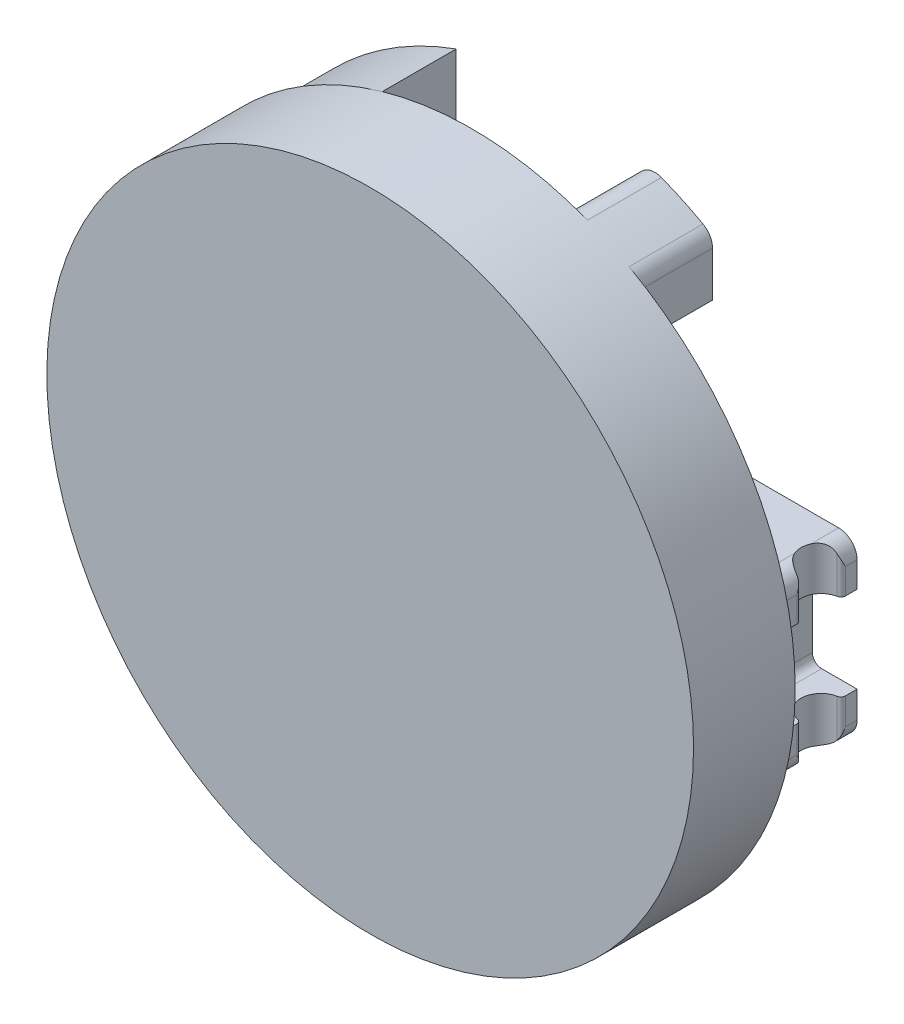
SolidWorks part; units mm, degrees
ref_plane "Front Plane" through (0, 0, 0) normal (0, 0, 1) x (1, 0, 0)
ref_plane "Top Plane" through (0, 0, 0) normal (0, 1, 0) x (1, 0, 0)
ref_plane "Right Plane" through (0, 0, 0) normal (1, 0, 0) x (0, 0, -1)
sketch "Sketch1" plane through (0, 0, 0) normal (0, 0, 1) x (1, 0, 0)
  circle A0 centre (0, 0) radius 35
extrude "Boss-Extrude1" add sketch "Sketch1" along normal blind 11
sketch "Sketch2" plane through (0, 0, 0) normal (0, 0, -1) x (-1, 0, 0)
  line L0 (0, 0) -> (0, -50000) construction
  line L1 (0, 0) -> (-50000, 0) construction
  line L2 (-9.8056, -33.5636) -> (-9.9241, -33.5636)
  line L3 (-31.7037, 9.437) -> (-18.0511, 9.437)
  line L4 (-33.7037, 7.437) -> (-33.7037, -7.5827)
  line L5 (-31.7037, -9.5827) -> (-18.0511, -9.5827)
  line L8 (-9.8056, 9.437) -> (-9.8056, 30.816)
  line L9 (-9.8056, 33.5636) -> (-9.9241, 33.5636)
  line L10 (-18.0511, 23.9568) -> (-18.0511, 28.8333)
  line L11 (-18.0511, -9.437) -> (-18.0511, -9.5827)
  line L14 (-9.8056, 9.437) -> (-9.8056, -30.816)
  line L15 (-33.7037, 4.6799) -> (-29.8596, 4.6799)
  line L17 (-33.7037, 0) -> (-28.8596, 0)
  line L18 (-28.8596, 3.6799) -> (-28.8596, -3.6799)
  line L19 (-33.7037, -4.6799) -> (-29.8596, -4.6799)
  line L20 (31.6711, 5.7176) -> (27.071, 5.7176)
  line L21 (25.071, 3.7176) -> (25.071, -3.7176)
  line L22 (31.6711, -5.7176) -> (27.071, -5.7176)
  line L24 (9.692, 9.437) -> (19.6111, 9.437)
  line L25 (9.692, 33.6313) -> (9.692, -33.6313)
  line L26 (19.6111, 9.437) -> (19.6111, -9.8056)
  line L27 (19.6111, -9.8056) -> (9.692, -9.8056)
  line L28 (-18.0511, -23.9568) -> (-18.0511, -28.8333)
  circle A0 centre (0, 0) radius 35 construction
  arc A2 (-17.0239, 30.5808) -> (-12.5211, 32.6837) centre (0, 0) cw
  arc A3 (-17.0239, -30.5808) -> (-12.5211, -32.6837) centre (0, 0) ccw
  arc A4 (-12.5211, 32.6837) -> (-9.8056, 30.816) centre (-11.8056, 30.816) cw
  arc A5 (-9.8056, -30.816) -> (-12.5211, -32.6837) centre (-11.8056, -30.816) cw
  arc A6 (-17.0239, -30.5808) -> (-18.0511, -28.8333) centre (-16.0511, -28.8333) cw
  arc A7 (-18.0511, 28.8333) -> (-17.0239, 30.5808) centre (-16.0511, 28.8333) cw
  arc A8 (-31.7037, -9.5827) -> (-33.7037, -7.5827) centre (-31.7037, -7.5827) cw
  arc A9 (-33.7037, 7.437) -> (-31.7037, 9.437) centre (-31.7037, 7.437) cw
  arc A10 (-29.8596, -4.6799) -> (-28.8596, -3.6799) centre (-29.8596, -3.6799) ccw
  arc A11 (-29.8596, 4.6799) -> (-28.8596, 3.6799) centre (-29.8596, 3.6799) cw
  arc A12 (-18.0511, 9.437) -> (-18.0511, 23.9568) centre (-18.0511, 16.6969) ccw
  arc A13 (-18.0511, -9.437) -> (-18.0511, -23.9568) centre (-18.0511, -16.6969) cw
  arc A14 (9.692, 33.6313) -> (32.6522, 6.9109) centre (-2.4188, 0) cw
  arc A15 (32.6522, -6.9109) -> (9.692, -33.6313) centre (-2.4188, 0) cw
  arc A16 (25.071, -3.7176) -> (27.071, -5.7176) centre (27.071, -3.7176) ccw
  arc A17 (25.071, 3.7176) -> (27.071, 5.7176) centre (27.071, 3.7176) cw
  arc A18 (32.6522, -6.9109) -> (31.6711, -5.7176) centre (31.6711, -6.7176) ccw
  arc A19 (31.6711, 5.7176) -> (32.6522, 6.9109) centre (31.6711, 6.7176) ccw
  point P35 (-18.0511, -29.9859)
  point P38 (-18.0511, 29.9859)
  point P43 (-33.7037, 9.437)
  point P46 (-28.8596, -4.6799)
  point P49 (-28.8596, 4.6799)
  point P57 (25.071, 0)
  point P60 (16.4912, -9.6941)
  point P64 (18.7197, -9.3599)
  point P65 (16.4912, -9.8056)
  point P68 (25.071, -5.7176)
  point P73 (25.071, 5.7176)
  point P76 (32.8664, -5.7176)
  point P79 (32.8664, 5.7176)
  circle M33 centre (0, 0) radius 35
  dimension "D1" = 2
  dimension "D2" = 1
  dimension "D3" = 2
  dimension "D4" = 1
extrude "Boss-Extrude2" add sketch "Sketch2" along normal blind 8 contours L11 A13 L28 A6 A5 L14 L8 A4 A7 L10 A12 L3 A9 L4 L15 A11 L18 A10 L19 A8 L5 M33 | L20 A19 A14 L25 L24 L26 L27 A15 A18 L22 A16 L21 A17 | L27 L26 L24 L25
sketch "Sketch4" plane through (0, 0, 0) normal (0, 0, -1) x (-1, 0, 0)
  line L0 (-9.8056, 9.437) -> (9.692, 9.437)
  line L1 (-9.8056, 30.816) -> (-9.8056, -30.816) construction
  line L2 (9.692, 33.6313) -> (9.692, -33.6313) construction
  line L3 (0, 0) -> (50000, 0) construction
  line L4 (-9.8056, 9.437) -> (-9.8056, -9.437)
  line L5 (-9.8056, 30.816) -> (-9.8056, -30.816) construction
  line L6 (9.692, 9.437) -> (9.692, -9.437)
  line L7 (-9.8056, -9.437) -> (9.692, -9.437)
  point P14 (9.692, 0)
  point P15 (-9.8056, 0)
extrude "Boss-Extrude3" add sketch "Sketch4" along normal blind 8
sketch "Sketch6" plane through (0, 0, -8) normal (0, 0, -1) x (-1, 0, 0)
  line L0 (0, 0) -> (-50000, 0) construction
  circle A0 centre (18.7569, 16.6969) radius 5.9189
  circle A1 centre (18.7569, -16.6969) radius 5.9189
extrude "Cut-Extrude1" cut sketch "Sketch6" against normal blind 5
sketch "Sketch7" plane through (0, 4.6799, 0) normal (0, -1, 0) x (1, 0, 0)
  line L0 (33.7037, -8) -> (33.7037, 0) construction
  line L1 (33.7037, 0) -> (29.8596, 0) construction
  line L2 (33.7037, -8) -> (33.7037, 0) construction
  point P7 (34.2777, -5.4438)
sketch "Sketch11" plane through (0, 4.6799, 0) normal (0, -1, 0) x (-1, 0, 0)
  line L0 (-33.7037, 1.4706) -> (-33.7037, 0)
  line L1 (-33.7037, 8) -> (-29.8596, 8)
  line L2 (-33.7037, 8) -> (-33.7037, 6.7459)
  line L3 (-33.7037, 0) -> (-29.8596, 0)
  line L4 (-29.8596, 8) -> (-29.8596, 0)
  line L5 (-33.7037, 6.7459) -> (-33.7037, 1.4706)
  arc A0 (-33.2969, 6.2547) -> (-33.2969, 1.9618) centre (-33.7037, 4.1083) cw
  arc A1 (-33.2969, 6.2547) -> (-33.7037, 6.7459) centre (-33.2037, 6.7459) cw
  arc A2 (-33.2969, 1.9618) -> (-33.7037, 1.4706) centre (-33.2037, 1.4706) ccw
  point P13 (-33.7037, 1.9236)
  line M12 (-33.7037, 8) -> (-33.7037, 0)
  dimension "D1" = 0.5
  dimension "D2" = 0.5
extrude "Cut-Extrude4" cut sketch "Sketch11" against normal blind 5 and the other way blind 16 contours A2 A0 A1 M12
